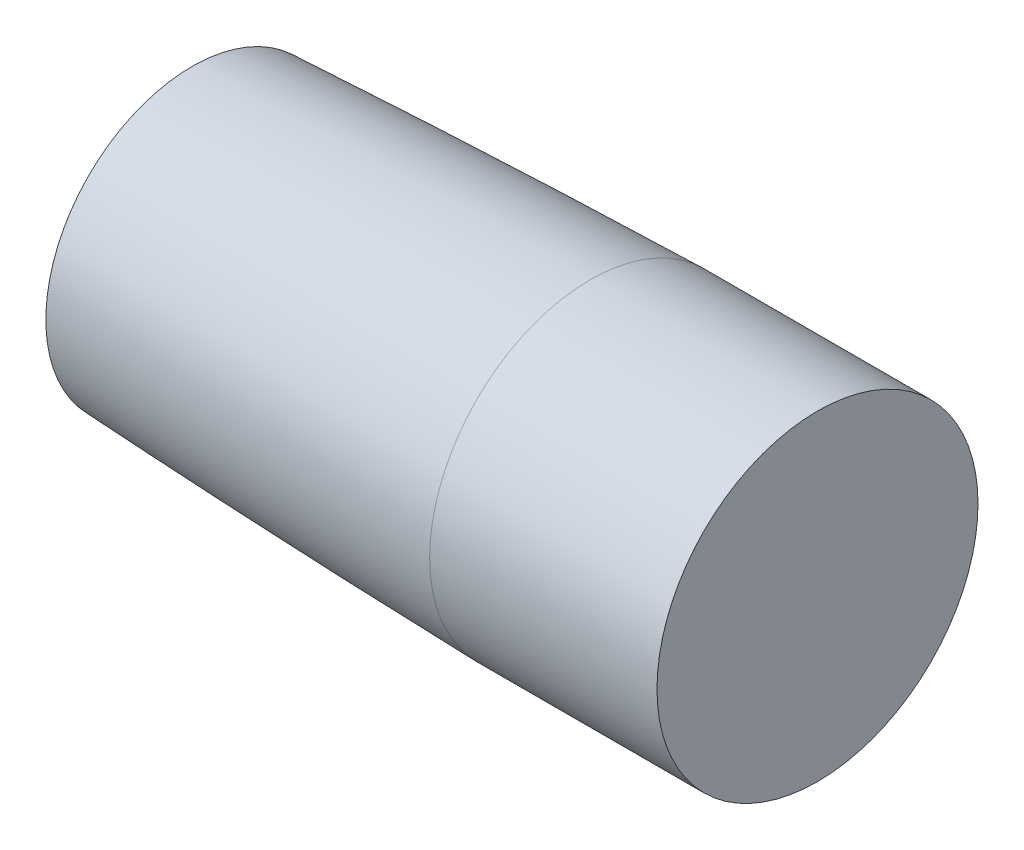
SolidWorks part; units mm, degrees
ref_plane "Front Plane" through (0, 0, 0) normal (0, 0, 1) x (1, 0, 0)
ref_plane "Top Plane" through (0, 0, 0) normal (0, 1, 0) x (1, 0, 0)
ref_plane "Right Plane" through (0, 0, 0) normal (1, 0, 0) x (0, 0, -1)
sketch "Sketch1" plane through (0, 0, 0) normal (0, 1, 0) x (1, 0, 0)
  line L0 (490.97, 47.801) -> (558.67, 47.801)
  line L1 (558.67, 47.801) -> (558.67, 0)
  line L2 (558.67, 0) -> (372.4, 0)
  line L3 (372.4, 0) -> (372.4, 43.5413)
  spline S0 degree 4 poles (360.5413, 42.9454) (361.4311, 42.9909) (363.1505, 43.0786) (365.0659, 43.1782) (370.8829, 43.4672) (373.0699, 43.5748) (378.9476, 43.8582) (382.3388, 44.0167) (386.7938, 44.2236) (390.6629, 44.398) (395.6096, 44.6181) (401.3943, 44.8678) (408.3126, 45.1578) (416.1855, 45.4734) (424.3365, 45.7866) (432.5052, 46.085) (440.6163, 46.3683) (448.8417, 46.6396) (456.8675, 46.8921) (465.2389, 47.1382) (472.3572, 47.3379) (479.3995, 47.5206) (484.0343, 47.6377) (489.7176, 47.7724) (492.0903, 47.8271) (497.4136, 47.946) (499.6102, 47.9913) (501.8491, 48.0381) (502.8706, 48.0589) knots 0 0 0 0 0 0.02078 0.04156 0.082616 0.111283 0.13995 0.168616 0.197283 0.225949 0.254616 0.30473 0.362063 0.419396 0.476729 0.534062 0.591395 0.648729 0.706062 0.763395 0.820728 0.859302 0.887968 0.916635 0.944256 0.971877 1 1 1 1 1 construction
  spline S1 degree 4 poles (372.4, 43.5413) (373.2493, 43.5828) (374.9692, 43.6664) (378.9476, 43.8582) (382.3388, 44.0167) (386.7938, 44.2236) (390.6629, 44.398) (395.6096, 44.6181) (401.3943, 44.8678) (408.3126, 45.1578) (416.1855, 45.4734) (424.3365, 45.7866) (432.5052, 46.085) (440.6163, 46.3683) (448.8417, 46.6396) (456.8675, 46.8921) (465.2389, 47.1382) (472.3572, 47.3379) (479.3995, 47.5206) (484.0343, 47.6377) (488.4468, 47.7423) (490.1199, 47.7814) (490.97, 47.801) knots 0.082616 0.082616 0.082616 0.082616 0.082616 0.111283 0.13995 0.168616 0.197283 0.225949 0.254616 0.30473 0.362063 0.419396 0.476729 0.534062 0.591395 0.648729 0.706062 0.763395 0.820728 0.859302 0.887968 0.916635 0.916635 0.916635 0.916635 0.916635
revolve "Revolve1" add sketch "Sketch1" angle 360 about L2
sketch "Sketch2" plane through (372.4, 0, 0) normal (-1, 0, 0) x (0, 0, 1)
  circle A0 centre (0, 0) radius 12.7
extrude "Cut-Extrude1" cut sketch "Sketch2" against normal blind 50.8
